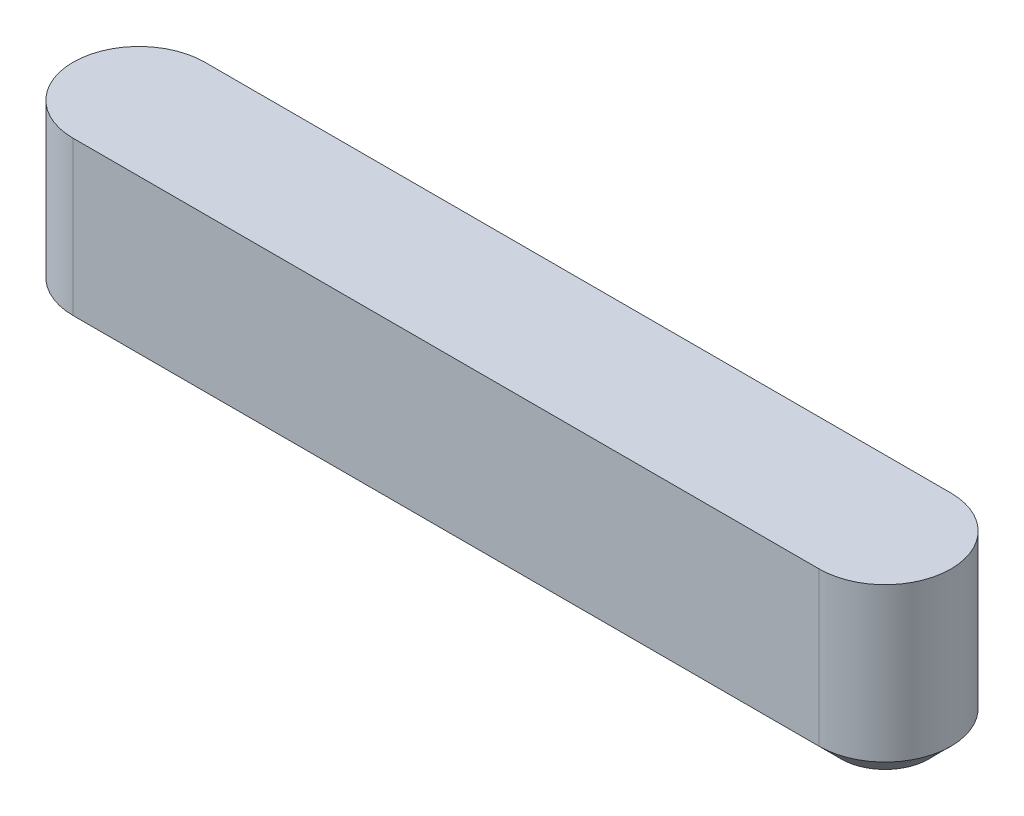
SolidWorks part; units mm, degrees
ref_plane "Front" through (0, 0, 0) normal (0, 0, 1) x (1, 0, 0)
ref_plane "Top" through (0, 0, 0) normal (0, 1, 0) x (1, 0, 0)
ref_plane "Right" through (0, 0, 0) normal (1, 0, 0) x (0, 0, -1)
sketch "草图1" plane through (0, 0, 0) normal (0, 1, 0) x (1, 0, 0)
  line L1 (-8.5, -1.5) -> (8.5, -1.5)
  line L3 (-8.5, 1.5) -> (8.5, 1.5)
  arc A0 (-8.5, 1.5) -> (-8.5, -1.5) centre (-8.5, 0) ccw
  arc A1 (8.5, -1.5) -> (8.5, 1.5) centre (8.5, 0) ccw
  point P0 (0, 0)
extrude "凸台-拉伸1" add sketch "草图1" along normal blind 4
chamfer "倒角1" distance 0.5 angle 45 4 edges at (0, 0, 1.5) (10, 0, 0) (-10, 0, 0) (0, 0, -1.5)
